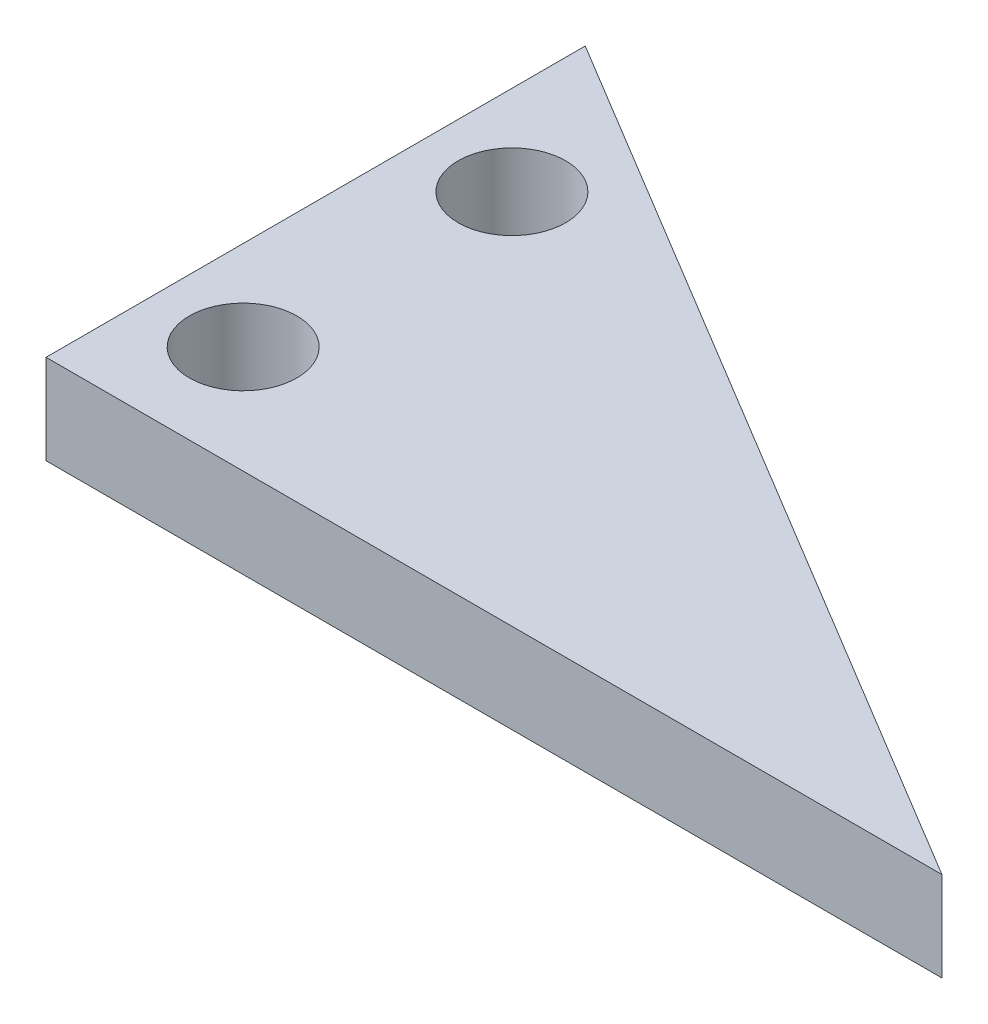
SolidWorks part; units mm, degrees
ref_plane "Front Plane" through (0, 0, 0) normal (0, 0, 1) x (1, 0, 0)
ref_plane "Top Plane" through (0, 0, 0) normal (0, 1, 0) x (1, 0, 0)
ref_plane "Right Plane" through (0, 0, 0) normal (1, 0, 0) x (0, 0, -1)
sketch "Sketch1" plane through (0, 0, 0) normal (0, 1, 0) x (1, 0, 0)
  line L0 (0, 0) -> (25.4, 0)
  line L1 (-55, 0) -> (55, 0) construction
  line L2 (0, 0) -> (0, 15.2859)
  line L3 (0, -55) -> (0, 55) construction
  line L4 (0, 15.2859) -> (25.4, 0)
  circle A0 centre (2.54, 3.048) radius 1.524
  circle A1 centre (2.54, 10.668) radius 1.524
  dimension "D3" = 3.048
  dimension "D1" = 25.4
  dimension "D2" = 15.2859
  dimension "D4" = 3.048
  dimension "D5" = 7.62
  dimension "D6" = 2.54
  dimension "D7" = 2.54
extrude "Boss-Extrude1" add sketch "Sketch1" along normal blind 2.54
